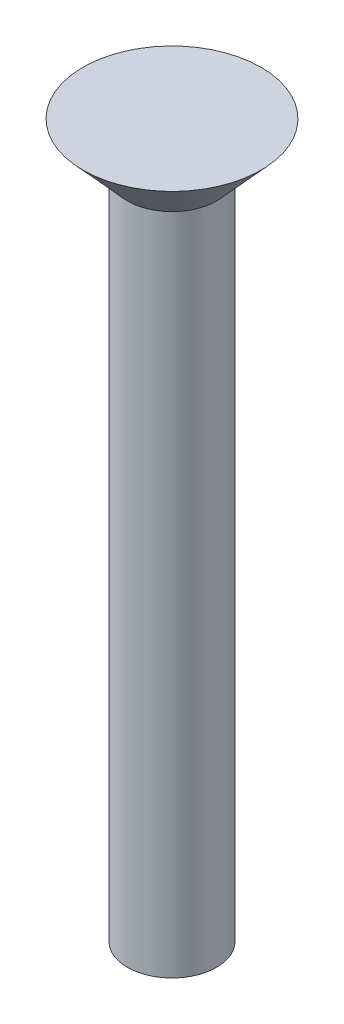
SolidWorks part; units mm, degrees
ref_plane "Plan de face" through (0, 0, 0) normal (0, 0, 1) x (1, 0, 0)
ref_plane "Plan de dessus" through (0, 0, 0) normal (0, 1, 0) x (1, 0, 0)
ref_plane "Plan de droite" through (0, 0, 0) normal (1, 0, 0) x (0, 0, -1)
sketch "Esquisse1" plane through (0, 0, 0) normal (0, 0, 1) x (1, 0, 0)
  line L0 (0, -35.1456) -> (5, -35.1456)
  line L1 (5, -35.1456) -> (5, 39.3544)
  line L2 (5, 39.3544) -> (10, 44.8544)
  line L3 (10, 44.8544) -> (0, 44.8544)
  line L4 (0, 44.8544) -> (0, -35.1456)
  dimension "D1" = 80
  dimension "D2" = 5
  dimension "D3" = 10
  dimension "D4" = 5.5
revolve "Révolution1" add sketch "Esquisse1" angle 360 about L4
